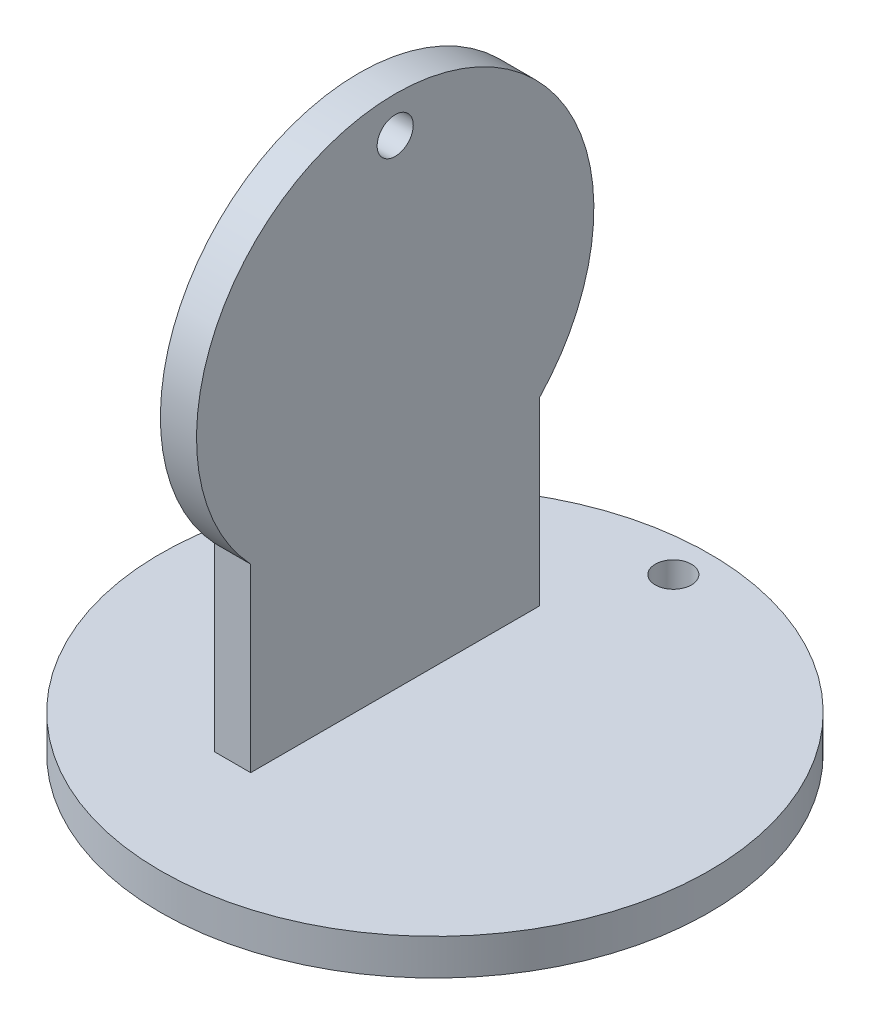
SolidWorks part; units mm, degrees
ref_plane "前视基准面" through (0, 0, 0) normal (0, 0, 1) x (1, 0, 0)
ref_plane "上视基准面" through (0, 0, 0) normal (0, 1, 0) x (1, 0, 0)
ref_plane "右视基准面" through (0, 0, 0) normal (1, 0, 0) x (0, 0, -1)
other "Configuration Table"
sketch "草图1" plane through (0, 0, 0) normal (0, 1, 0) x (1, 0, 0)
  circle A0 centre (0, 0) radius 38
  circle A1 centre (0, 0) radius 33 construction
  circle A2 centre (0, 33) radius 2.5
  dimension "D1" = 76
  dimension "D3" = 66
  dimension "D4" = 5
extrude "凸台-拉伸1" add sketch "草图1" along normal blind 5
ref_plane "基准面1" through (-10.5, 0, 0) normal (1, 0, 0) x (0, 0, -1)
sketch "草图5" plane through (-10.5, 0, 0) normal (1, 0, 0) x (0, 0, -1)
  line L0 (0, 17.5) -> (0, 0) construction
  line L1 (-20, 30) -> (20, 30) construction
  line L2 (-20, 30) -> (-20, 5)
  line L3 (-20, 5) -> (20, 5)
  line L4 (20, 30) -> (20, 5)
  line L5 (-20, 30) -> (20, 5) construction
  line L6 (-20, 5) -> (20, 30) construction
  line L7 (38, 5) -> (-38, 5) construction
  line L8 (0, 48.8746) -> (0, 17.5) construction
  arc A0 (20, 30) -> (-20, 30) centre (0, 48.8746) ccw
  circle A1 centre (0, 48.8746) radius 22.5 construction
  circle A2 centre (0, 71.3746) radius 2.5
  point P0 (0, 17.5)
  dimension "D2" = 27.5
  dimension "D4" = 45
  dimension "D5" = 5
  dimension "D1" = 40
  dimension "D3" = 25
extrude "凸台-拉伸3" add sketch "草图5" along normal blind 5
